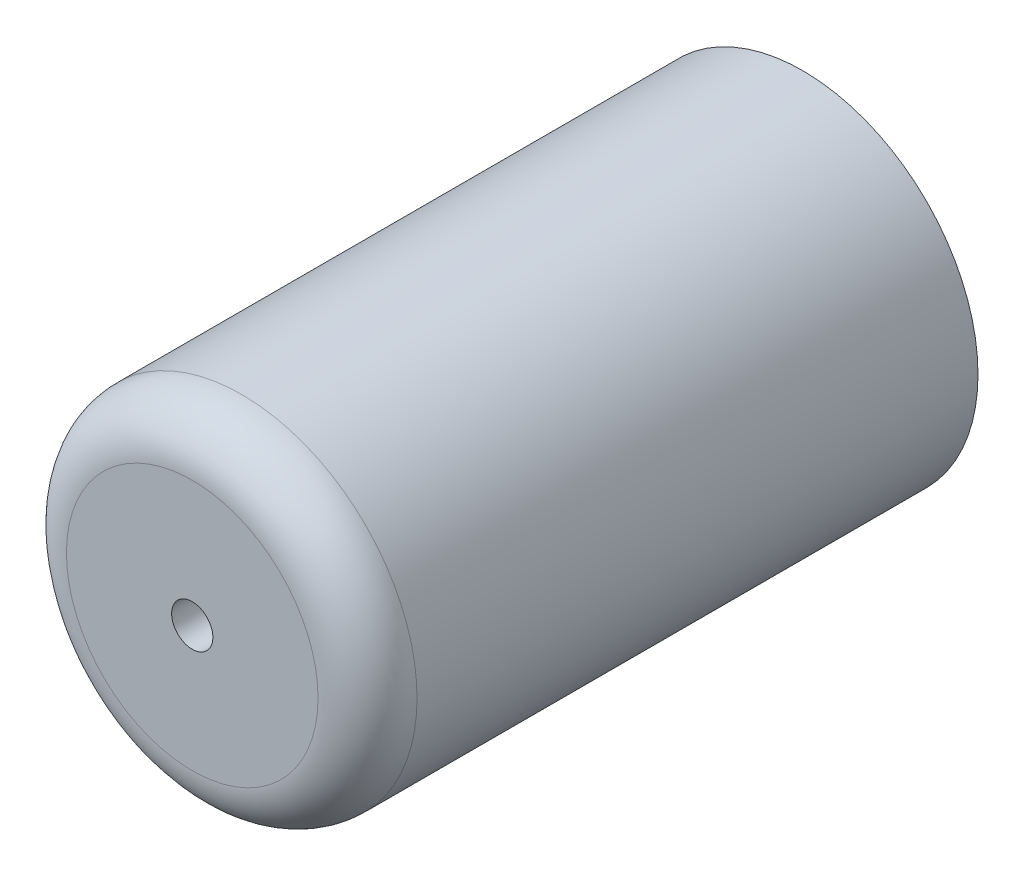
SolidWorks part; units mm, degrees
material "PVC Rigid"
ref_plane "Front Plane" through (0, 0, 0) normal (0, 0, 1) x (1, 0, 0)
ref_plane "Top Plane" through (0, 0, 0) normal (0, 1, 0) x (1, 0, 0)
ref_plane "Right Plane" through (0, 0, 0) normal (1, 0, 0) x (0, 0, -1)
sketch "Sketch1" plane through (0, 0, 0) normal (0, 0, 1) x (1, 0, 0)
  circle A0 centre (0, 0) radius 21.25
  circle A1 centre (0, 0) radius 2.5
  dimension "D1" = 42.5
  dimension "D2" = 5
extrude "Boss-Extrude1" add sketch "Sketch1" along normal blind 74
fillet "Fillet1" radius 6 1 edges at (21.25, 0, 74)
sketch "Sketch2" plane through (0, 0, 0) normal (0, 0, -1) x (-1, 0, 0)
  circle A0 centre (0, 0) radius 4.445
  circle A1 centre (0, 0) radius 17.145
  dimension "D1" = 34.29
  dimension "D2" = 8.89
extrude "Cut-Extrude1" cut sketch "Sketch2" against normal blind 65
